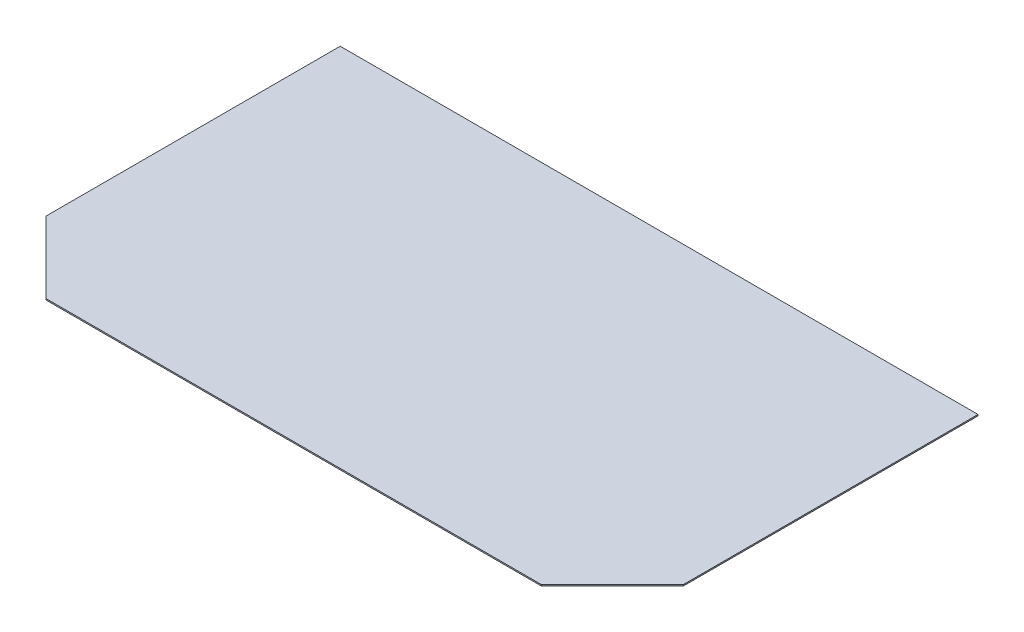
SolidWorks part; units mm, degrees
material "Germanium"
ref_plane "Front Plane" through (0, 0, 0) normal (0, 0, 1) x (1, 0, 0)
ref_plane "Top Plane" through (0, 0, 0) normal (0, 1, 0) x (1, 0, 0)
ref_plane "Right Plane" through (0, 0, 0) normal (1, 0, 0) x (0, 0, -1)
sketch "Sketch1" plane through (0, 0, 0) normal (0, 1, 0) x (1, 0, 0)
  line L0 (0, 0) -> (0, -31.7831)
  line L1 (0, 0) -> (68.9, 0)
  line L4 (68.9, 0) -> (68.9, -31.7831)
  line L6 (68.9, -31.7831) -> (61.1831, -39.5)
  line L7 (61.1831, -39.5) -> (7.7169, -39.5)
  line L8 (7.7169, -39.5) -> (0, -31.7831)
  dimension "D1" = 135
  dimension "D4" = 39.5
  dimension "D2" = 7.7169
  dimension "D5" = 68.9
  dimension "D6" = 135
extrude "Doped Germanium" add sketch "Sketch1" along normal blind 0.14
equation "\"Major dim\"= \"Minor dim\" * 4"
equation "\"A\"= ( ( \"Major dim\"+\"Minor dim\" + \"Minor dim\" )  ^ 2 )  -  ( 2 * \"Minor dim\" * \"Minor dim\" ) "
